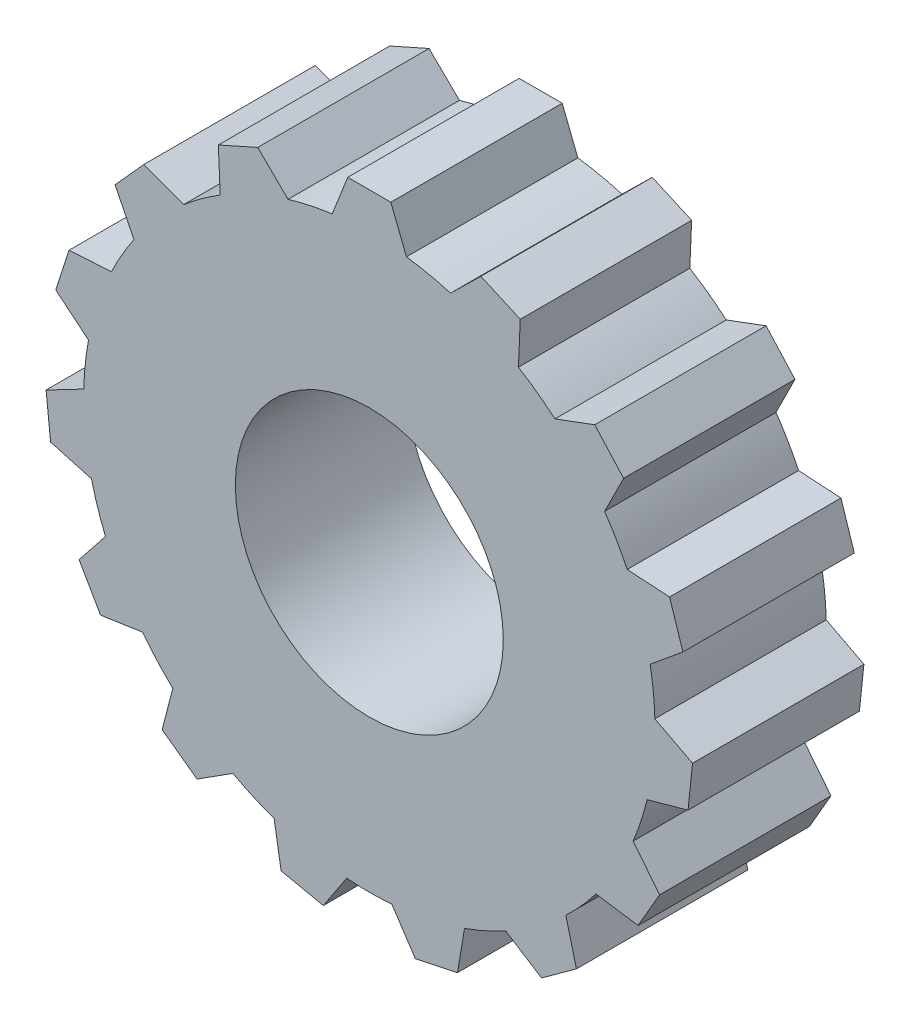
SolidWorks part; units mm, degrees
ref_plane "Front Plane" through (0, 0, 0) normal (0, 0, 1) x (1, 0, 0)
ref_plane "Top Plane" through (0, 0, 0) normal (0, 1, 0) x (1, 0, 0)
ref_plane "Right Plane" through (0, 0, 0) normal (1, 0, 0) x (0, 0, -1)
sketch "Sketch1" plane through (0, 0, 0) normal (0, 0, 1) x (1, 0, 0)
  line L0 (6.5017, 49.5755) -> (3.7723, 56.4945)
  line L1 (-3.7723, 56.4945) -> (3.7723, 56.4945)
  line L2 (-6.5017, 49.5755) -> (-3.7723, 56.4945)
  line L3 (26.1038, 42.645) -> (26.4246, 50.076)
  line L4 (19.5322, 53.1446) -> (26.4246, 50.076)
  line L5 (14.2246, 47.9339) -> (19.5322, 53.1446)
  line L6 (41.1922, 28.3408) -> (44.5078, 34.9989)
  line L7 (39.4595, 40.6056) -> (44.5078, 34.9989)
  line L8 (32.4913, 38.0042) -> (39.4595, 40.6056)
  line L9 (49.1582, 9.1362) -> (54.8952, 13.8701)
  line L10 (52.5638, 21.0454) -> (54.8952, 13.8701)
  line L11 (45.1399, 21.5032) -> (52.5638, 21.0454)
  line L12 (48.6243, -11.6481) -> (55.7907, -9.6569)
  line L13 (56.5794, -2.1537) -> (55.7907, -9.6569)
  line L14 (49.9835, 1.284) -> (56.5794, -2.1537)
  line L15 (39.6828, -30.4184) -> (47.0395, -31.5142)
  line L16 (50.8118, -24.9804) -> (47.0395, -31.5142)
  line L17 (46.1845, -19.1571) -> (50.8118, -24.9804)
  line L18 (23.8797, -43.929) -> (30.1548, -47.9223)
  line L19 (36.2585, -43.4877) -> (30.1548, -47.9223)
  line L20 (34.3997, -36.2858) -> (36.2585, -43.4877)
  line L21 (3.9477, -49.8439) -> (8.056, -56.0443)
  line L22 (15.4357, -54.4757) -> (8.056, -56.0443)
  line L23 (16.6669, -47.1404) -> (15.4357, -54.4757)
  line L24 (-16.6669, -47.1404) -> (-15.4357, -54.4757)
  line L25 (-8.056, -56.0443) -> (-15.4357, -54.4757)
  line L26 (-3.9477, -49.8439) -> (-8.056, -56.0443)
  line L27 (-34.3997, -36.2858) -> (-36.2585, -43.4877)
  line L28 (-30.1548, -47.9223) -> (-36.2585, -43.4877)
  line L29 (-23.8797, -43.929) -> (-30.1548, -47.9223)
  line L30 (-46.1845, -19.1571) -> (-50.8118, -24.9804)
  line L31 (-47.0395, -31.5142) -> (-50.8118, -24.9804)
  line L32 (-39.6828, -30.4184) -> (-47.0395, -31.5142)
  line L33 (-49.9835, 1.284) -> (-56.5794, -2.1537)
  line L34 (-55.7907, -9.6569) -> (-56.5794, -2.1537)
  line L35 (-48.6243, -11.6481) -> (-55.7907, -9.6569)
  line L36 (-45.1399, 21.5032) -> (-52.5638, 21.0454)
  line L37 (-54.8952, 13.8701) -> (-52.5638, 21.0454)
  line L38 (-49.1582, 9.1362) -> (-54.8952, 13.8701)
  line L39 (-32.4913, 38.0042) -> (-39.4595, 40.6056)
  line L40 (-44.5078, 34.9989) -> (-39.4595, 40.6056)
  line L41 (-41.1922, 28.3408) -> (-44.5078, 34.9989)
  line L42 (-14.2246, 47.9339) -> (-19.5322, 53.1446)
  line L43 (-26.4246, 50.076) -> (-19.5322, 53.1446)
  line L44 (-26.1038, 42.645) -> (-26.4246, 50.076)
  arc A2 (-26.1038, 42.645) -> (-32.4913, 38.0042) centre (0, 0) ccw
  arc A3 (-6.5017, 49.5755) -> (-14.2246, 47.9339) centre (0, 0) ccw
  arc A4 (14.2246, 47.9339) -> (6.5017, 49.5755) centre (0, 0) ccw
  arc A5 (32.4913, 38.0042) -> (26.1038, 42.645) centre (0, 0) ccw
  arc A6 (45.1399, 21.5032) -> (41.1922, 28.3408) centre (0, 0) ccw
  arc A7 (49.9835, 1.284) -> (49.1582, 9.1362) centre (0, 0) ccw
  arc A8 (46.1845, -19.1571) -> (48.6243, -11.6481) centre (0, 0) ccw
  arc A9 (34.3997, -36.2858) -> (39.6828, -30.4184) centre (0, 0) ccw
  arc A10 (16.6669, -47.1404) -> (23.8797, -43.929) centre (0, 0) ccw
  arc A11 (-3.9477, -49.8439) -> (3.9477, -49.8439) centre (0, 0) ccw
  arc A12 (-23.8797, -43.929) -> (-16.6669, -47.1404) centre (0, 0) ccw
  arc A13 (-39.6828, -30.4184) -> (-34.3997, -36.2858) centre (0, 0) ccw
  arc A14 (-48.6243, -11.6481) -> (-46.1845, -19.1571) centre (0, 0) ccw
  arc A15 (-49.1582, 9.1362) -> (-49.9835, 1.284) centre (0, 0) ccw
  arc A16 (-41.1922, 28.3408) -> (-45.1399, 21.5032) centre (0, 0) ccw
  point P66 (0, 0)
  dimension "D1" = 100
  dimension "D2" = 15
extrude "Boss-Extrude1" add sketch "Sketch1" along normal blind 30
sketch "Sketch2" plane through (0, 0, 30) normal (0, 0, 1) x (1, 0, 0)
  circle A0 centre (0, 0) radius 23.4502
extrude "Cut-Extrude1" cut sketch "Sketch2" against normal blind 30 contours A0
